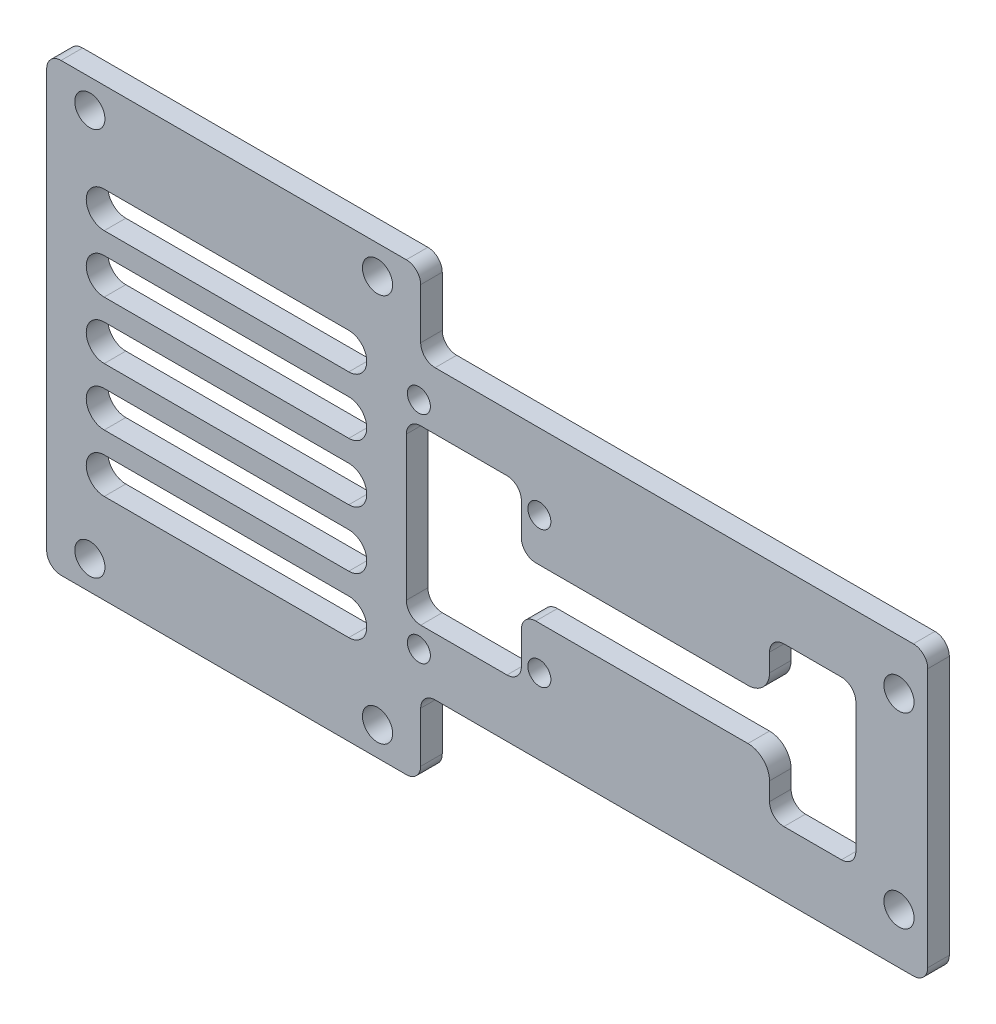
SolidWorks part; units mm, degrees
material "Thornel Mat VMA"
ref_plane "前视基准面" through (0, 0, 0) normal (0, 0, 1) x (1, 0, 0)
ref_plane "上视基准面" through (0, 0, 0) normal (0, 1, 0) x (1, 0, 0)
ref_plane "右视基准面" through (0, 0, 0) normal (1, 0, 0) x (0, 0, -1)
sketch "草图1" plane through (0, 0, 0) normal (0, 0, 1) x (1, 0, 0)
  line L0 (-26, 0) -> (-26, -62)
  line L1 (-26, -62) -> (26, -62)
  line L2 (26, -62) -> (26, -51)
  line L3 (26, -51) -> (96.5, -51)
  line L4 (96.5, -7) -> (96.5, -55) construction
  line L5 (96.5, -51) -> (96.5, -11)
  line L6 (96.5, -15.4142) -> (96.5, -12) construction
  line L7 (96.5, -11) -> (26, -11)
  line L8 (26, -11) -> (26, 0)
  line L9 (26, 0) -> (-26, 0)
  line L10 (-26, -31) -> (136.1922, -31) construction
  line L11 (68, -34.5) -> (68, -27.5)
  line L12 (68, -27.5) -> (40, -27.5)
  line L13 (40, -27.5) -> (40, -19)
  line L14 (40, -19) -> (24, -19)
  line L15 (24, -19) -> (24, -43)
  line L20 (68, -33.7) -> (68, -28.3) construction
  line L21 (68, -34.5) -> (40, -34.5)
  line L22 (40, -34.5) -> (40, -43)
  line L23 (40, -43) -> (24, -43)
  circle A0 centre (-20, -4) radius 2.1
  circle A1 centre (20, -4) radius 2.1
  circle A2 centre (-20, -58) radius 2.1
  circle A3 centre (20, -58) radius 2.1
  circle A4 centre (42.5, -21.5) radius 1.6
  circle A5 centre (42.5, -40.5) radius 1.6
  circle A6 centre (92.5, -18) radius 2.1
  circle A7 centre (92.5, -44) radius 2.1
  circle A8 centre (92.5, -44) radius 2 construction
  circle A9 centre (92.5, -18) radius 2 construction
  circle A10 centre (42.5, -40.5) radius 1.5 construction
  circle A11 centre (42.5, -21.5) radius 1.5 construction
  circle A12 centre (25.75, -16) radius 1.25 construction
  circle A13 centre (25.75, -46) radius 1.25 construction
  circle A14 centre (25.75, -16) radius 1.25 construction
  circle A15 centre (25.75, -46) radius 1.25 construction
  circle A16 centre (25.75, -46) radius 1.6
  circle A17 centre (25.75, -16) radius 1.6
  point P52 (68, -31)
  point P55 (24, -31)
  dimension "D3" = 4.2
  dimension "D4" = 4.2
  dimension "D5" = 4.2
  dimension "D6" = 4.2
  dimension "D7" = 3.2
  dimension "D8" = 3.2
  dimension "D9" = 4.2
  dimension "D10" = 4.2
  dimension "D15" = 3.2
  dimension "D16" = 3.2
  dimension "D1" = 20
  dimension "D2" = 20
  dimension "D11" = 3.5
  dimension "D12" = 28
  dimension "D13" = 12
  dimension "D14" = 16
extrude "凸台-拉伸1" add sketch "草图1" along normal blind 3
fillet "圆角1" radius 2 16 edges at (40, -19, 1.5) (24, -19, 1.5) (24, -43, 1.5) (40, -43, 1.5) (40, -34.5, 1.5) (40, -27.5, 1.5) (68, -27.5, 1.5) (68, -34.5, 1.5) (26, -62, 1.5) (26, -51, 1.5) (96.5, -51, 1.5) (96.5, -11, 1.5) (26, -11, 1.5) (26, 0, 1.5) (-26, -62, 1.5) (-26, 0, 1.5)
sketch "草图2" plane through (0, 0, 3) normal (0, 0, 1) x (1, 0, 0)
  line L0 (-26, -31) -> (96.5, -31) construction
  line L1 (-26, -2) -> (-26, -60) construction
  line L2 (96.5, -49) -> (96.5, -13) construction
  line L3 (-18, -31) -> (16, -31) construction
  line L4 (-18, -28.5) -> (16, -28.5)
  line L5 (-18, -33.5) -> (16, -33.5)
  line L6 (24, -21) -> (24, -41) construction
  line L7 (-18, -23) -> (16, -23) construction
  line L8 (-18, -20.5) -> (16, -20.5)
  line L9 (-18, -25.5) -> (16, -25.5)
  line L10 (-18, -15) -> (16, -15) construction
  line L11 (-18, -12.5) -> (16, -12.5)
  line L12 (-18, -17.5) -> (16, -17.5)
  line L13 (-18, -39) -> (16, -39) construction
  line L14 (-18, -36.5) -> (16, -36.5)
  line L15 (-18, -41.5) -> (16, -41.5)
  line L16 (-18, -47) -> (16, -47) construction
  line L17 (-18, -44.5) -> (16, -44.5)
  line L18 (-18, -49.5) -> (16, -49.5)
  line L19 (74.5, -22) -> (74.5, -40)
  line L20 (76.5, -42) -> (84.5, -42)
  line L21 (86.5, -40) -> (86.5, -22)
  line L22 (84.5, -20) -> (76.5, -20)
  arc A0 (-18, -28.5) -> (-18, -33.5) centre (-18, -31) ccw
  arc A1 (16, -33.5) -> (16, -28.5) centre (16, -31) ccw
  arc A2 (-18, -20.5) -> (-18, -25.5) centre (-18, -23) ccw
  arc A3 (16, -25.5) -> (16, -20.5) centre (16, -23) ccw
  arc A4 (-18, -12.5) -> (-18, -17.5) centre (-18, -15) ccw
  arc A5 (16, -17.5) -> (16, -12.5) centre (16, -15) ccw
  arc A6 (-18, -36.5) -> (-18, -41.5) centre (-18, -39) ccw
  arc A7 (16, -41.5) -> (16, -36.5) centre (16, -39) ccw
  arc A8 (-18, -44.5) -> (-18, -49.5) centre (-18, -47) ccw
  arc A9 (16, -49.5) -> (16, -44.5) centre (16, -47) ccw
  arc A10 (76.5, -20) -> (74.5, -22) centre (76.5, -22) ccw
  arc A11 (74.5, -40) -> (76.5, -42) centre (76.5, -40) ccw
  arc A12 (84.5, -42) -> (86.5, -40) centre (84.5, -40) ccw
  arc A13 (86.5, -22) -> (84.5, -20) centre (84.5, -22) ccw
  point P8 (-1, -31)
  point P19 (-1, -23)
  point P26 (-1, -15)
  point P33 (-1, -39)
  point P40 (-1, -47)
  point P51 (74.5, -20)
  point P58 (86.5, -20)
  dimension "D12" = 2
  dimension "D1" = 8
  dimension "D2" = 8
  dimension "D3" = 5
  dimension "D5" = 8
  dimension "D7" = 8
  dimension "D8" = 11
  dimension "D9" = 11
  dimension "D10" = 10
  dimension "D11" = 12
  dimension "D4" = 3
  dimension "D6" = 3
extrude "切除-拉伸1" cut sketch "草图2" against normal through all
sketch "草图3" plane through (0, 0, 3) normal (0, 0, 1) x (1, 0, 0)
  line L0 (66, -27.5) -> (74.5, -27.5)
  line L1 (74.5, -22) -> (74.5, -40) construction
  line L2 (66, -34.5) -> (74.5, -34.5)
  line L3 (74.5, -34.5) -> (74.5, -27.5)
  line L4 (66, -27.5) -> (66, -34.5)
extrude "切除-拉伸2" cut sketch "草图3" against normal through all
fillet "圆角2" radius 3 2 edges at (74.5, -34.5, 1.5) (74.5, -27.5, 1.5)
